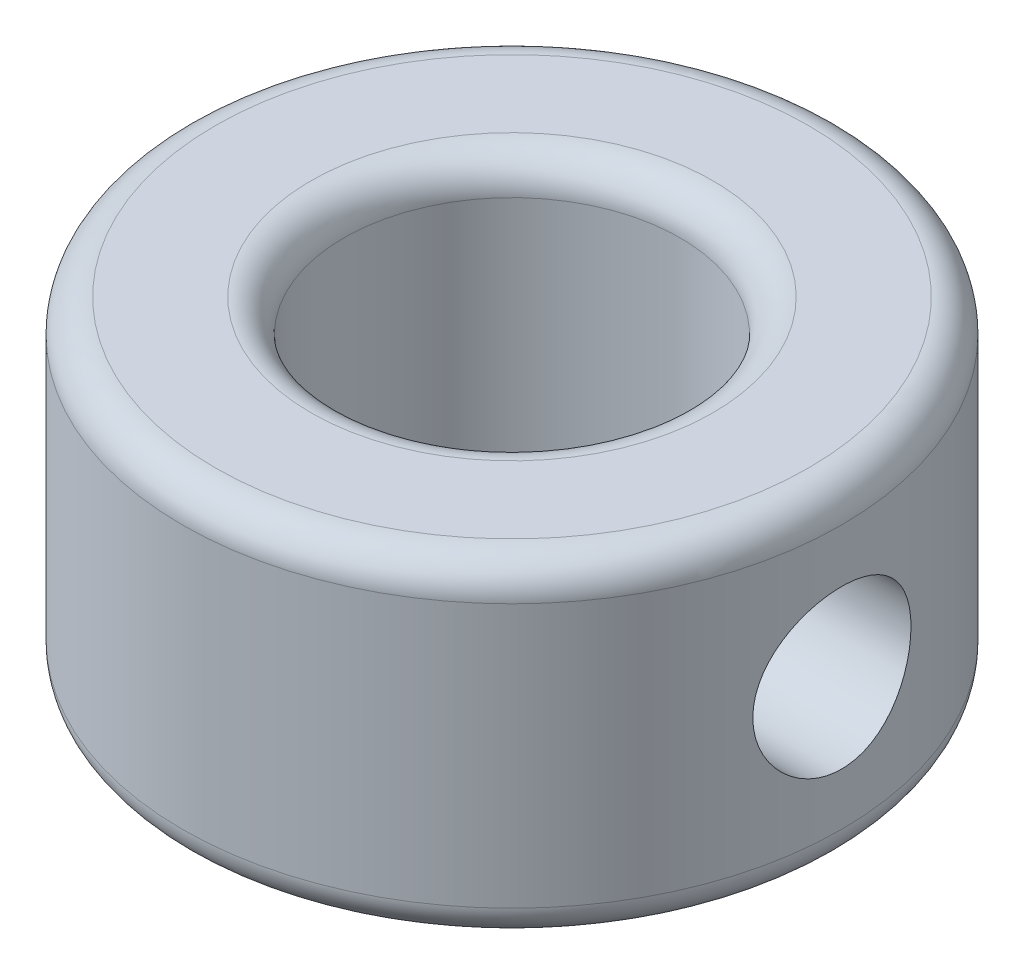
SolidWorks part; units mm, degrees
material "ABS"
ref_plane "Front Plane" through (0, 0, 0) normal (0, 0, 1) x (1, 0, 0)
ref_plane "Top Plane" through (0, 0, 0) normal (0, 1, 0) x (1, 0, 0)
ref_plane "Right Plane" through (0, 0, 0) normal (1, 0, 0) x (0, 0, -1)
sketch "Sketch1" plane through (0, 0, 0) normal (0, 1, 0) x (1, 0, 0)
  circle A0 centre (0, 0) radius 5
  circle A1 centre (0, 0) radius 2.55
  dimension "D1" = 5.1
  dimension "D2" = 10
extrude "Boss-Extrude1" add sketch "Sketch1" along normal blind 5
fillet "Fillet1" radius 0.5 4 edges at (0, 0, 2.55) (0, 0, 5) (0, 5, 2.55) (0, 5, 5)
hole_wizard "Ø2.5mm Dowel Hole1" positions "3DSketch1" profile "Sketch2" hole size "Ø2.5" standard "ANSI Metric"
sketch3d "3DSketch1"
  point P0 (5, 2.4917, 0)
sketch "Sketch2" plane through (5, 2.4917, 0) normal (0, 1, 0) x (0, 0, -1)
  line L0 (0, 0) -> (0, 5.721)
  line L1 (0, 5.721) -> (1.2, 5)
  line L2 (1.2, 5) -> (1.2, 0)
  line L5 (1.2, 0) -> (0, 0)
  line L10 (0, 5.721) -> (-1.2, 5) construction
  line L11 (0, -6.35) -> (0, 107.95) construction
  dimension "Hole Dia." = 2.4
  dimension "Hole Depth" = 5
  dimension "Drill Angle" = 118
